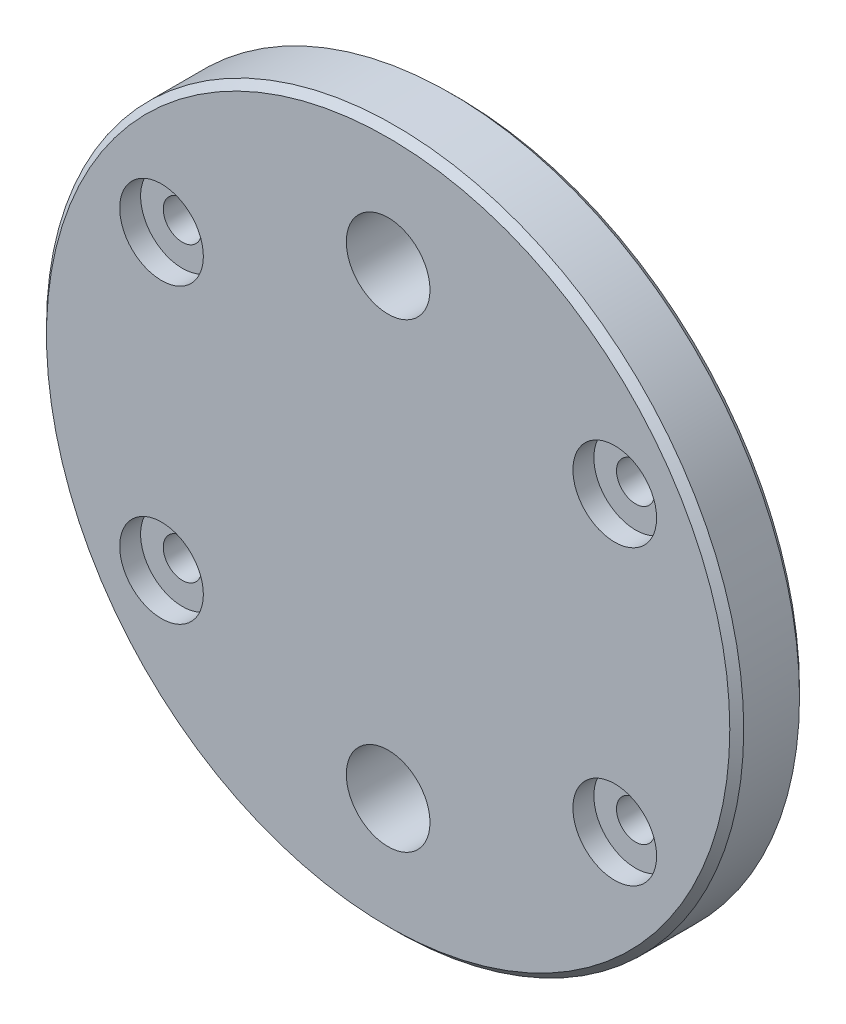
SolidWorks part; units mm, degrees
ref_plane "Front Plane" through (0, 0, 0) normal (0, 0, 1) x (1, 0, 0)
ref_plane "Top Plane" through (0, 0, 0) normal (0, 1, 0) x (1, 0, 0)
ref_plane "Right Plane" through (0, 0, 0) normal (1, 0, 0) x (0, 0, -1)
sketch "Sketch1" plane through (0, 0, 0) normal (0, 0, 1) x (1, 0, 0)
  circle A0 centre (0, 0) radius 50
  dimension "D1" = 100
extrude "Boss-Extrude1" add sketch "Sketch1" along normal blind 10
hole_wizard "CBORE for M6 Hex Socket Head Cap Screw1" positions "Sketch3" profile "Sketch4" counterbore size "M6" standard "ISO" end condition through all
sketch "Sketch3" plane through (0, 0, 10) normal (0, 0, 1) x (1, 0, 0)
  point P0 (-32.5, 21)
  point P2 (32.5, 21)
  point P4 (32.5, -21)
  point P6 (-32.5, -21)
  dimension "D1" = 21
  dimension "D2" = 42
  dimension "D3" = 32.5
  dimension "D4" = 65
sketch "Sketch4" plane through (-32.5, 21, 10) normal (1, 0, 0) x (0, -1, 0)
  line L0 (0, 0) -> (0, 10)
  line L1 (0, 10) -> (2.75, 10)
  line L3 (2.75, 10) -> (2.75, 3)
  line L4 (2.75, 3) -> (6, 3)
  line L5 (6, 3) -> (6, 0)
  line L7 (6, 0) -> (0, 0)
  line L11 (0, -6.35) -> (0, 107.95) construction
  dimension "Thru Hole Dia." = 5.5
  dimension "Thru Hole Depth" = 10
  dimension "C'Bore Dia." = 12
  dimension "C'Bore Depth" = 3
hole_wizard "Ø12.0 (12) Diameter Hole1" positions "Sketch5" profile "Sketch6" hole size "Ø12.0" standard "ISO" end condition through all
sketch "Sketch5" plane through (0, 0, 10) normal (0, 0, 1) x (1, 0, 0)
  circle A0 centre (-32.5, 21) radius 6 construction
  circle A1 centre (32.5, -21) radius 2.75 construction
  point P0 (0, 33.07)
  point P2 (0, -33.07)
  dimension "D1" = 33.07
  dimension "D2" = 66.14
  dimension "D3" = 32.5
  dimension "D4" = 32.5
sketch "Sketch6" plane through (0, 33.07, 10) normal (1, 0, 0) x (0, -1, 0)
  line L0 (0, 0) -> (0, 10)
  line L1 (0, 10) -> (6, 10)
  line L2 (6, 10) -> (6, 0)
  line L5 (6, 0) -> (0, 0)
  line L11 (0, -6.35) -> (0, 107.95) construction
  dimension "Thru Hole Dia." = 12
  dimension "Thru Hole Depth" = 10
hole_wizard "CSK for M3 Hex Socket Countersunk Cap Screw1" positions "Sketch7" profile "Sketch8" countersink size "M3" standard "ISO" end condition through all
sketch "Sketch7" plane through (0, 0, 0) normal (0, 0, -1) x (-1, 0, 0)
  point P0 (-32.5, 21)
  point P3 (-32.5, -21)
  point P6 (32.5, -21)
  point P9 (32.5, 21)
sketch "Sketch8" plane through (32.5, 21, 0) normal (1, 0, 0) x (0, 1, 0)
  line L0 (0, 0) -> (0, 10)
  line L1 (0, 10) -> (2.75, 10)
  line L2 (2.75, 10) -> (2.75, 2.85)
  line L3 (2.75, 2.85) -> (5.6, 0)
  line L5 (5.6, 0) -> (0, 0)
  line L6 (-2.75, 2.85) -> (-5.6, 0) construction
  line L11 (0, -6.35) -> (0, 107.95) construction
  dimension "Thru Hole Dia." = 5.5
  dimension "Thru Hole Depth" = 10
  dimension "Near C'Sink Dia." = 11.2
  dimension "Near C'Sink Angle" = 90
chamfer "Chamfer1" distance 1 angle 45 2 edges at (50, 0, 0) (50, 0, 10)
